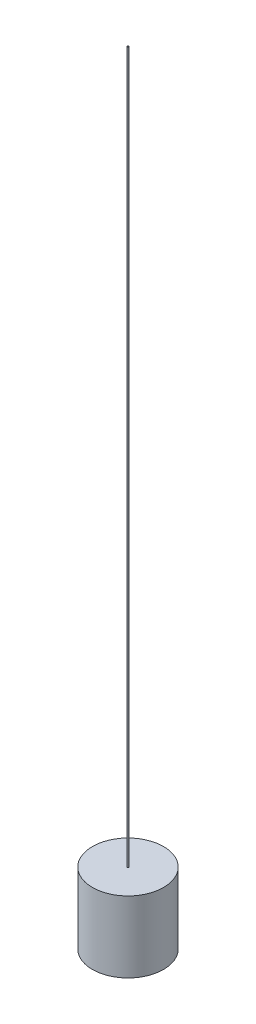
SolidWorks part; units mm, degrees
ref_plane "正面" through (0, 0, 0) normal (0, 0, 1) x (1, 0, 0)
ref_plane "平面" through (0, 0, 0) normal (0, 1, 0) x (1, 0, 0)
ref_plane "右側面" through (0, 0, 0) normal (1, 0, 0) x (0, 0, -1)
sketch "ｽｹｯﾁ1" plane through (0, 0, 0) normal (0, 0, 1) x (1, 0, 0)
  line L1 (0, 0) -> (-500, 0)
  line L2 (0, 0) -> (0, -1000)
  line L3 (0, -1000) -> (-500, -1000)
  line L4 (-500, 0) -> (-500, -1000)
  line L5 (0, 0) -> (-10, 0)
  line L6 (0, 0) -> (0, 10000)
  line L7 (0, 10000) -> (-10, 10000)
  line L8 (-10, 0) -> (-10, 10000)
revolve "回転1" add sketch "ｽｹｯﾁ1" angle 360 about L2
